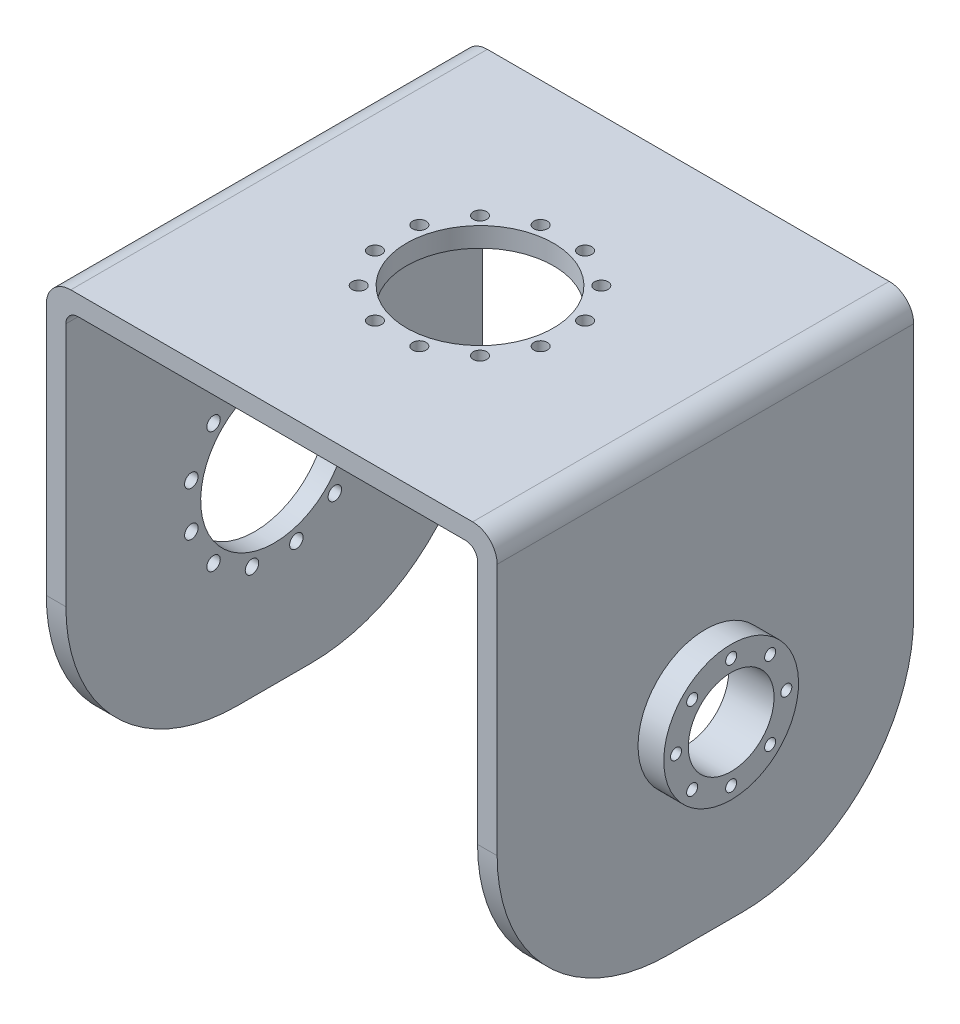
SolidWorks part; units mm, degrees
material "6061 合金"
ref_plane "前视基准面" through (0, 0, 0) normal (0, 0, 1) x (1, 0, 0)
ref_plane "上视基准面" through (0, 0, 0) normal (0, 1, 0) x (1, 0, 0)
ref_plane "右视基准面" through (0, 0, 0) normal (1, 0, 0) x (0, 0, -1)
other "Configuration Table"
sketch "草图1" plane through (0, 0, 0) normal (0, 0, 1) x (1, 0, 0)
  line L0 (-168, 0) -> (0, 0)
  line L1 (0, 0) -> (0, -175)
  line L3 (8, -175) -> (8, 8)
  line L4 (8, 8) -> (-168, 8)
  line L6 (0, -175) -> (8, -175)
  line L12 (-168, 8) -> (-176, 8)
  line L13 (-168, 0) -> (-168, -175)
  line L14 (-168, -175) -> (-176, -175)
  line L15 (-176, 8) -> (-176, -175)
  dimension "D1" = 8
  dimension "D2" = 8
  dimension "D3" = 184
  dimension "D5" = 183
  dimension "D6" = 8
  dimension "D8" = 8
extrude "凸台-拉伸1" add sketch "草图1" along normal blind 170
sketch "草图2" plane through (0, 8, 0) normal (0, 1, 0) x (1, 0, 0)
  line L0 (-216.3195, -85) -> (51.5119, -85) construction
  line L1 (8, -170) -> (-176, -170) construction
  line L2 (8, 0) -> (-176, 0) construction
  line L7 (-84, -75.3242) -> (-84, -92.2023) construction
  line L8 (8, -170) -> (8, 0) construction
  line L9 (-176, -170) -> (-176, 0) construction
  circle A2 centre (-84, -85) radius 30
  dimension "D3" = 60
extrude "切除-拉伸1" cut sketch "草图2" against normal blind 180 contours A2 L0 | L0 A2
sketch "草图3" plane through (8, 0, 0) normal (1, 0, 0) x (0, 0, -1)
  line L0 (-85, 25.6845) -> (-85, -173.3318) construction
  line L1 (0, -175) -> (0, 8) construction
  line L2 (-170, -175) -> (-170, 8) construction
  line L3 (-170, -175) -> (0, -175) construction
  line L4 (0, 0) -> (-209.686, 0) construction
  circle A0 centre (-85, -95) radius 17.5
  dimension "D1" = 35
  dimension "D2" = 80
extrude "切除-拉伸2" cut sketch "草图3" against normal through all both and the other way through all contours A0
fillet "圆角1" radius 70 4 edges at (-172, -175, 170) (-172, -175, 0) (4, -175, 0) (4, -175, 170)
fillet "圆角2" radius 5 2 edges at (-168, 0, 85) (0, 0, 85)
fillet "圆角3" radius 10 2 edges at (8, 8, 85) (-176, 8, 85)
sketch "草图6" plane through (-176, 0, 0) normal (-1, 0, 0) x (0, 0, 1)
  circle A0 centre (85, -95) radius 30
  dimension "D1" = 60
extrude "切除-拉伸6" cut sketch "草图6" against normal blind 39
sketch "草图7" plane through (0, 0, 0) normal (-1, 0, 0) x (0, 0, 1)
  circle A0 centre (85, -95) radius 13
  dimension "D1" = 26
extrude "切除-拉伸7" [suppressed] cut sketch "草图7" against normal blind 0.7
sketch "草图8" plane through (8, 0, 0) normal (1, 0, 0) x (0, 0, -1)
  line L0 (-85, -95) -> (-13.3452, -95) construction
  line L1 (-85, -95) -> (-143.0331, -95) construction
  circle A0 centre (-55, -95) radius 2.5
  circle A1 centre (-115, -95) radius 2.5
  dimension "D1" = 5
  dimension "D2" = 5
  dimension "D3" = 30
  dimension "D4" = 30
extrude "切除-拉伸8" [suppressed] cut sketch "草图8" against normal blind 10
sketch "草图9" [suppressed] plane through (8, 0, 0) normal (1, 0, 0) x (0, 0, -1)
  circle A0 centre (-55, -95) radius 6
  circle A1 centre (-115, -95) radius 6
  dimension "D1" = 12
  dimension "D2" = 12
extrude "切除-拉伸9" [suppressed] cut sketch "草图9" against normal blind 4
sketch "草图12" plane through (-176, 0, 0) normal (-1, 0, 0) x (0, 0, 1)
  line L0 (85, -95) -> (85, -143.8801) construction
  line L1 (85, -95) -> (97.9809, -143.4455) construction
  circle A0 centre (94.0587, -128.8074) radius 2.75
  circle A1 centre (75.9413, -128.8074) radius 2.75
  circle A2 centre (60.2513, -119.7487) radius 2.75
  circle A3 centre (51.1926, -104.0587) radius 2.75
  circle A4 centre (51.1926, -85.9413) radius 2.75
  circle A5 centre (60.2513, -70.2513) radius 2.75
  circle A6 centre (75.9413, -61.1926) radius 2.75
  circle A7 centre (94.0587, -61.1926) radius 2.75
  circle A8 centre (109.7487, -70.2513) radius 2.75
  circle A9 centre (118.8074, -85.9413) radius 2.75
  circle A10 centre (118.8074, -104.0587) radius 2.75
  circle A11 centre (109.7487, -119.7487) radius 2.75
  point P31 (85, -95)
  dimension "D2" = 5.5
  dimension "D1" = 15
  dimension "D3" = 35
  dimension "D4" = 12
extrude "切除-拉伸12" cut sketch "草图12" against normal blind 10
sketch "草图14" plane through (8, 0, 0) normal (1, 0, 0) x (0, 0, -1)
  circle A0 centre (-85, -95) radius 27.5
  circle A1 centre (-85, -95) radius 17.5 construction
  circle A2 centre (-85, -95) radius 17.5
  dimension "D1" = 55
extrude "凸台-拉伸2" add sketch "草图14" along normal blind 10.5
sketch "草图13" plane through (8, 0, 0) normal (1, 0, 0) x (0, 0, -1)
  line L0 (-85, -95) -> (-85, -50) construction
  circle A0 centre (-85, -95) radius 22.5 construction
  circle A1 centre (-85, -72.5) radius 2.25
  circle A2 centre (-69.0901, -79.0901) radius 2.25
  circle A3 centre (-62.5, -95) radius 2.25
  circle A4 centre (-69.0901, -110.9099) radius 2.25
  circle A5 centre (-85, -117.5) radius 2.25
  circle A6 centre (-100.9099, -110.9099) radius 2.25
  circle A7 centre (-107.5, -95) radius 2.25
  circle A8 centre (-100.9099, -79.0901) radius 2.25
  point P22 (-85, -95)
  dimension "D1" = 45
  dimension "D2" = 4.5
  dimension "D3" = 8
extrude "切除-拉伸13" cut sketch "草图13" against normal mid plane 30
sketch "草图15" plane through (0, 8, 0) normal (0, 1, 0) x (1, 0, 0)
  line L0 (-84, -85) -> (-84, -144.7778) construction
  line L1 (-84, -85) -> (-74.9413, -118.8074) construction
  circle A0 centre (-74.9413, -118.8074) radius 2.75
  circle A1 centre (-93.0587, -118.8074) radius 2.75
  circle A2 centre (-108.7487, -109.7487) radius 2.75
  circle A3 centre (-117.8074, -94.0587) radius 2.75
  circle A4 centre (-117.8074, -75.9413) radius 2.75
  circle A5 centre (-108.7487, -60.2513) radius 2.75
  circle A6 centre (-93.0587, -51.1926) radius 2.75
  circle A7 centre (-74.9413, -51.1926) radius 2.75
  circle A8 centre (-59.2513, -60.2513) radius 2.75
  circle A9 centre (-50.1926, -75.9413) radius 2.75
  circle A10 centre (-50.1926, -94.0587) radius 2.75
  circle A11 centre (-59.2513, -109.7487) radius 2.75
  point P29 (-84, -85)
  dimension "D1" = 5.5
  dimension "D2" = 35
  dimension "D3" = 15
  dimension "D4" = 12
extrude "切除-拉伸14" cut sketch "草图15" against normal blind 10
